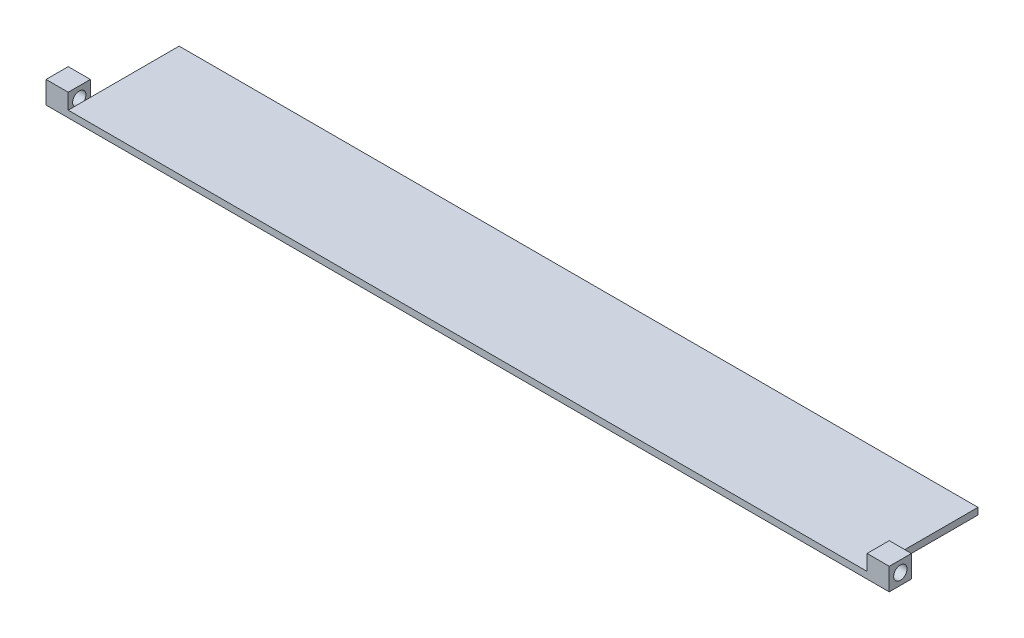
SolidWorks part; units mm, degrees
ref_plane "Ebene vorne" through (0, 0, 0) normal (0, 0, 1) x (1, 0, 0)
ref_plane "Ebene oben" through (0, 0, 0) normal (0, 1, 0) x (1, 0, 0)
ref_plane "Ebene rechts" through (0, 0, 0) normal (1, 0, 0) x (0, 0, -1)
sketch "Skizze1" plane through (0, 0, 0) normal (0, 1, 0) x (1, 0, 0)
  line L1 (-90, -12.5) -> (90, -12.5)
  line L2 (-90, -12.5) -> (-90, 12.5)
  line L3 (-90, 12.5) -> (90, 12.5)
  line L4 (90, -12.5) -> (90, 12.5)
  line L5 (-90, -12.5) -> (90, 12.5) construction
  line L6 (-90, 12.5) -> (90, -12.5) construction
  point P0 (0, 0)
  dimension "D1" = 180
  dimension "D2" = 25
extrude "Aufsatz-Linear austragen1" add sketch "Skizze1" along normal blind 1.5
sketch "Skizze2" plane through (90, 0, 0) normal (1, 0, 0) x (0, 0, -1)
  line L1 (-12.5, 0) -> (-7.5, 0)
  line L2 (-12.5, 0) -> (-12.5, 5)
  line L3 (-12.5, 5) -> (-7.5, 5)
  line L4 (-7.5, 0) -> (-7.5, 5)
  dimension "D1" = 5
  dimension "D2" = 5
extrude "Aufsatz-Linear austragen2" add sketch "Skizze2" along normal blind 5
sketch "Skizze3" plane through (95, 0, 0) normal (1, 0, 0) x (0, 0, -1)
  line L0 (-7.5, 0) -> (-7.5, 5) construction
  line L1 (-7.5, 5) -> (-12.5, 5) construction
  circle A0 centre (-10, 2.5) radius 1.5
  dimension "D3" = 3
  dimension "D1" = 2.5
  dimension "D2" = 2.5
extrude "Schnitt-Linear austragen1" cut sketch "Skizze3" against normal blind 5
sketch "Skizze4" plane through (-90, 0, 0) normal (-1, 0, 0) x (0, 0, 1)
  line L1 (12.5, 0) -> (7.5, 0)
  line L2 (12.5, 0) -> (12.5, 5)
  line L3 (12.5, 5) -> (7.5, 5)
  line L4 (7.5, 0) -> (7.5, 5)
extrude "Aufsatz-Linear austragen3" add sketch "Skizze4" along normal blind 5
sketch "Skizze5" plane through (-95, 0, 0) normal (-1, 0, 0) x (0, 0, 1)
  line L0 (12.5, 0) -> (12.5, 5) construction
  line L1 (12.5, 5) -> (7.5, 5) construction
  circle A0 centre (10, 2.5) radius 1.5
  dimension "D3" = 3
  dimension "D1" = 2.5
  dimension "D2" = 2.5
extrude "Schnitt-Linear austragen2" cut sketch "Skizze5" against normal blind 5
